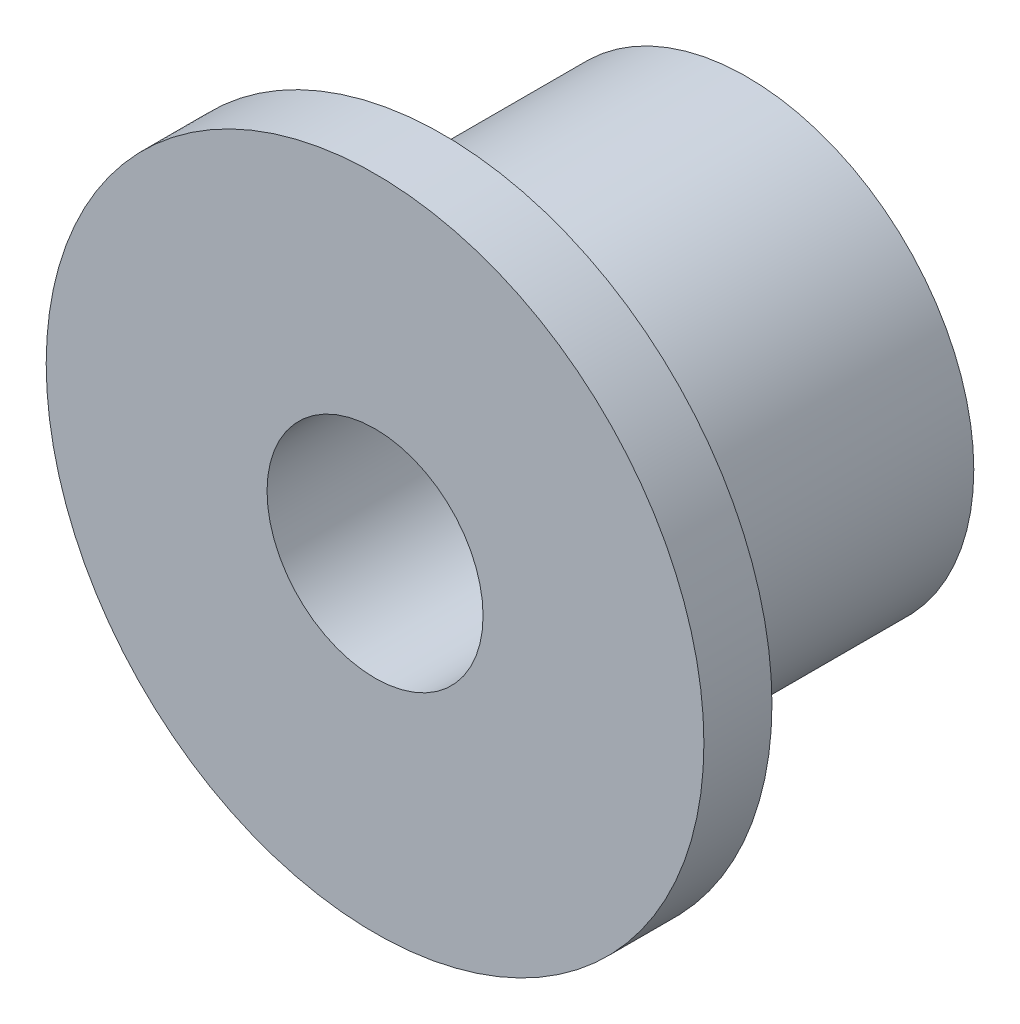
SolidWorks part; units mm, degrees
ref_plane "Front" through (0, 0, 0) normal (0, 0, 1) x (1, 0, 0)
ref_plane "Top" through (0, 0, 0) normal (0, 1, 0) x (1, 0, 0)
ref_plane "Right" through (0, 0, 0) normal (1, 0, 0) x (0, 0, -1)
sketch "Sketch1" plane through (0, 0, 0) normal (0, 0, 1) x (1, 0, 0)
  circle A0 centre (0, 0) radius 10
  dimension "D1" = 20
extrude "Boss-Extrude1" add sketch "Sketch1" along normal blind 13.4
sketch "Sketch2" plane through (0, 0, 13.4) normal (0, 0, 1) x (1, 0, 0)
  circle A0 centre (0, 0) radius 14.5
  dimension "D1" = 29
extrude "Boss-Extrude2" add sketch "Sketch2" along normal blind 3
sketch "Sketch3" plane through (0, 0, 16.4) normal (0, 0, 1) x (1, 0, 0)
  circle A0 centre (0, 0) radius 4.7625
  dimension "D1" = 9.525
extrude "Cut-Extrude1" cut sketch "Sketch3" against normal up to surface (16.4 mm away) up to face at (10, 0, 0)
sketch "Sketch4" plane through (0, 0, 0) normal (1, 0, 0) x (0, 0, -1)
  line L1 (5, -5) -> (-5, -5) construction
  line L2 (5, -5) -> (5, 5) construction
  line L3 (5, 5) -> (-5, 5) construction
  line L4 (-5, -5) -> (-5, 5) construction
  line L5 (5, -5) -> (-5, 5) construction
  line L6 (5, 5) -> (-5, -5) construction
  circle A0 centre (-5, 0) radius 1.8987
  point P0 (0, 0)
  dimension "D3" = 3.7973
  dimension "D1" = 10
  dimension "D2" = 10
extrude "Cut-Extrude2" cut sketch "Sketch4" against normal up to surface (10 mm away)
